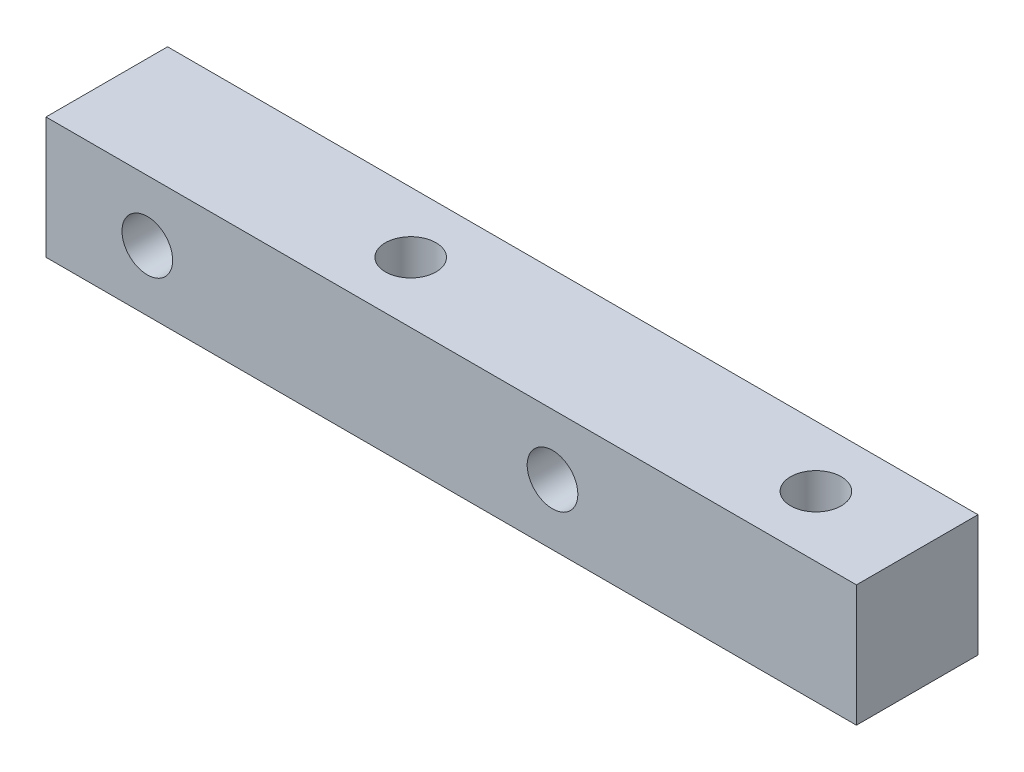
SolidWorks part; units mm, degrees
material "6060 合金"
ref_plane "前视基准面" through (0, 0, 0) normal (0, 0, 1) x (1, 0, 0)
ref_plane "上视基准面" through (0, 0, 0) normal (0, 1, 0) x (1, 0, 0)
ref_plane "右视基准面" through (0, 0, 0) normal (1, 0, 0) x (0, 0, -1)
sketch "草图1" plane through (0, 0, 0) normal (0, 0, 1) x (1, 0, 0)
  line L1 (-20, 3) -> (20, 3)
  line L2 (-20, 3) -> (-20, -3)
  line L3 (-20, -3) -> (20, -3)
  line L4 (20, 3) -> (20, -3)
  line L5 (-20, 3) -> (20, -3) construction
  line L6 (-20, -3) -> (20, 3) construction
  point P0 (0, 0)
  dimension "D1" = 6
  dimension "D2" = 40
extrude "凸台-拉伸1" add sketch "草图1" along normal blind 6
hole_wizard "M3 螺纹孔1" positions "草图2" profile "草图3" tap size "M3" standard "GB"
sketch "草图2" plane through (0, 0, 6) normal (0, 0, 1) x (1, 0, 0)
  point P0 (-15, 0)
  point P2 (5, 0)
  dimension "D1" = 5
  dimension "D2" = 15
sketch "草图3" plane through (-15, 0, 6) normal (1, 0, 0) x (0, -1, 0)
  line L0 (0, 0) -> (0, 11.2511)
  line L1 (0, 11.2511) -> (1.25, 10.5)
  line L2 (1.25, 10.5) -> (1.25, 0)
  line L5 (1.25, 0) -> (0, 0)
  line L10 (0, 11.2511) -> (-1.25, 10.5) construction
  line L11 (0, -6.35) -> (0, 107.95) construction
  dimension "螺纹孔钻头直径" = 2.5
  dimension "螺纹孔钻头深度" = 10.5
  dimension "导头角度" = 118
cosmetic thread "孔螺蚊线1"
cosmetic thread "孔螺蚊线2"
hole_wizard "M3 螺纹孔2" positions "草图4" profile "草图5" tap size "M3" standard "GB"
sketch "草图4" plane through (0, 3, 0) normal (0, 1, 0) x (1, 0, 0)
  line L0 (20, 0) -> (-20, 0) construction
  point P0 (-5, -3)
  point P2 (15, -3)
  dimension "D1" = 20
  dimension "D2" = 5
  dimension "D3" = 3
sketch "草图5" plane through (-5, 3, 3) normal (1, 0, 0) x (0, 0, 1)
  line L0 (0, 0) -> (0, 11.2511)
  line L1 (0, 11.2511) -> (1.25, 10.5)
  line L2 (1.25, 10.5) -> (1.25, 0)
  line L5 (1.25, 0) -> (0, 0)
  line L10 (0, 11.2511) -> (-1.25, 10.5) construction
  line L11 (0, -6.35) -> (0, 107.95) construction
  dimension "螺纹孔钻头直径" = 2.5
  dimension "螺纹孔钻头深度" = 10.5
  dimension "导头角度" = 118
cosmetic thread "孔螺蚊线3"
cosmetic thread "孔螺蚊线4"
